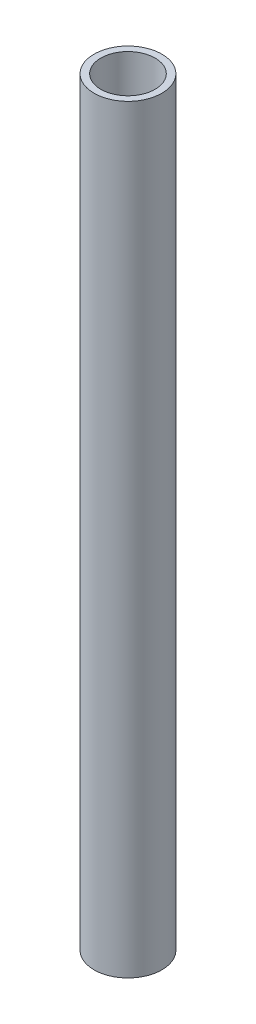
SolidWorks part; units mm, degrees
material "ABS"
ref_plane "Спереди" through (0, 0, 0) normal (0, 0, 1) x (1, 0, 0)
ref_plane "Сверху" through (0, 0, 0) normal (0, 1, 0) x (1, 0, 0)
ref_plane "Справа" through (0, 0, 0) normal (1, 0, 0) x (0, 0, -1)
sketch "Эскиз1" plane through (0, 0, 0) normal (0, 1, 0) x (1, 0, 0)
  circle A0 centre (0, 0) radius 1
  circle A1 centre (0, 0) radius 1.25
  dimension "D1" = 2
  dimension "D2" = 2.5
extrude "Бобышка-Вытянуть1" add sketch "Эскиз1" along normal blind 28
